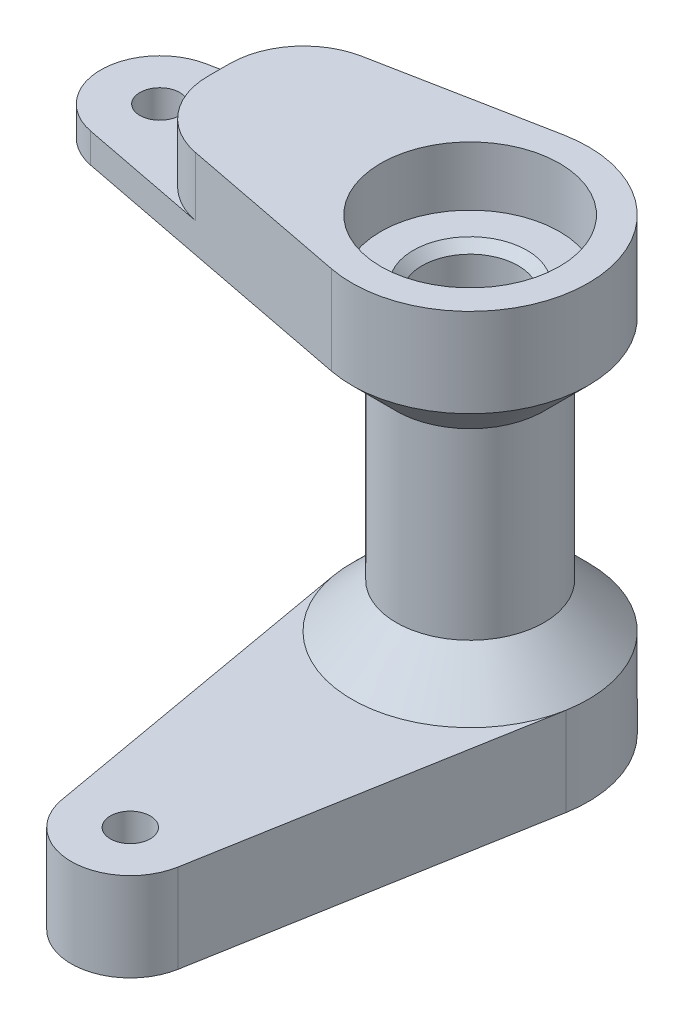
SolidWorks part; units mm, degrees
material "PET"
ref_plane "Plan de face" through (0, 0, 0) normal (0, 0, 1) x (1, 0, 0)
ref_plane "Plan de dessus" through (0, 0, 0) normal (0, 1, 0) x (1, 0, 0)
ref_plane "Plan de droite" through (0, 0, 0) normal (1, 0, 0) x (0, 0, -1)
sketch "Esquisse1" plane through (0, 0, 0) normal (0, 0, 1) x (1, 0, 0)
  line L0 (0, -1.1442) -> (0, 29.6304) construction
  line L1 (-6.05, 0) -> (-6.05, 4)
  line L2 (-6.05, 4) -> (-3.85, 4)
  line L3 (-3.25, 4.6) -> (-3.25, 25.8)
  line L4 (-3.85, 26.4) -> (-6.05, 26.4)
  line L5 (-6.05, 26.4) -> (-6.05, 30.4)
  line L6 (-6.05, 30.4) -> (-8, 30.4)
  line L7 (-8, 30.4) -> (-8, 24.4)
  line L8 (-8, 24.4) -> (-5, 21.4)
  line L9 (-5, 21.4) -> (-5, 9)
  line L10 (-5, 9) -> (-8, 6)
  line L11 (-8, 6) -> (-8, 0)
  line L12 (-8, 0) -> (-6.05, 0)
  line L13 (-3.25, 25.8) -> (-3.85, 26.4)
  line L14 (-3.85, 4) -> (-3.25, 4.6)
  point P6 (-3.25, 4)
  point P7 (-3.25, 26.4)
  point P21 (-7.025, 0)
  dimension "D1" = 16
  dimension "D2" = 6.5
  dimension "D3" = 12.1
  dimension "D4" = 30.4
  dimension "D5" = 6
  dimension "D6" = 4
  dimension "D7" = 10
  dimension "D8" = 45
revolve "Révolution1" add sketch "Esquisse1" angle 360 about L0
sketch "Esquisse2" plane through (0, 0, 0) normal (0, 1, 0) x (1, 0, 0)
  line L0 (-7.8781, -1.3913) -> (-3.939, -23.6957)
  line L2 (3.939, -23.6957) -> (7.8781, -1.3913)
  circle A0 centre (0, -23) radius 1.35
  arc A1 (3.939, -23.6957) -> (-3.939, -23.6957) centre (0, -23) cw
  arc A6 (-7.8781, -1.3913) -> (7.8781, -1.3913) centre (0, 0) ccw
  circle A7 centre (0, 0) radius 8 construction
  dimension "D1" = 4
  dimension "D2" = 23
  dimension "D3" = 2.7
extrude "Boss.-Extru.2" add sketch "Esquisse2" along normal up to vertex (6 mm away) up to point (-8, 6, 0)
sketch "Esquisse3" plane through (0, 30.4, 0) normal (0, 1, 0) x (1, 0, 0)
  line L0 (-21.7619, -3.9268) -> (-1.5238, -7.8535)
  line L1 (-21.7619, 3.9268) -> (-1.5238, 7.8535)
  line L2 (0, 0) -> (0, 8) construction
  line L3 (0, 0) -> (-21, 0) construction
  circle A0 centre (-21, 0) radius 1.35
  circle A1 centre (0, -23) radius 1.35 construction
  arc A2 (-21.7619, 3.9268) -> (-21.7619, -3.9268) centre (-21, 0) ccw
  arc A3 (-3.939, -23.6957) -> (3.939, -23.6957) centre (0, -23) ccw construction
  arc A4 (-1.5238, 7.8535) -> (-1.5238, -7.8535) centre (0, 0) ccw
  circle A5 centre (0, 0) radius 8 construction
  dimension "D1" = 21
  dimension "D2" = 270
extrude "Boss.-Extru.3" add sketch "Esquisse3" against normal up to vertex (6 mm away) up to point (-8, 24.4, 0)
sketch "Esquisse4" plane through (0, 0, 0) normal (0, 0, 1) x (1, 0, 0)
  line L0 (-21.7619, 24.4) -> (-1.5238, 24.4) construction
  line L1 (-25, 30.4) -> (-17, 30.4)
  line L2 (-25, 30.4) -> (-25, 26.4)
  line L3 (-25, 26.4) -> (-17, 26.4)
  line L4 (-17, 30.4) -> (-17, 26.4)
  dimension "D1" = 2
  dimension "D2" = 8
extrude "Enlèv. mat.-Extru.1" cut sketch "Esquisse4" against normal up to next and the other way up to next
fillet "Congé1" radius 5 2 edges at (-17, 28.4, 4.8507) (-17, 28.4, -4.8507)
